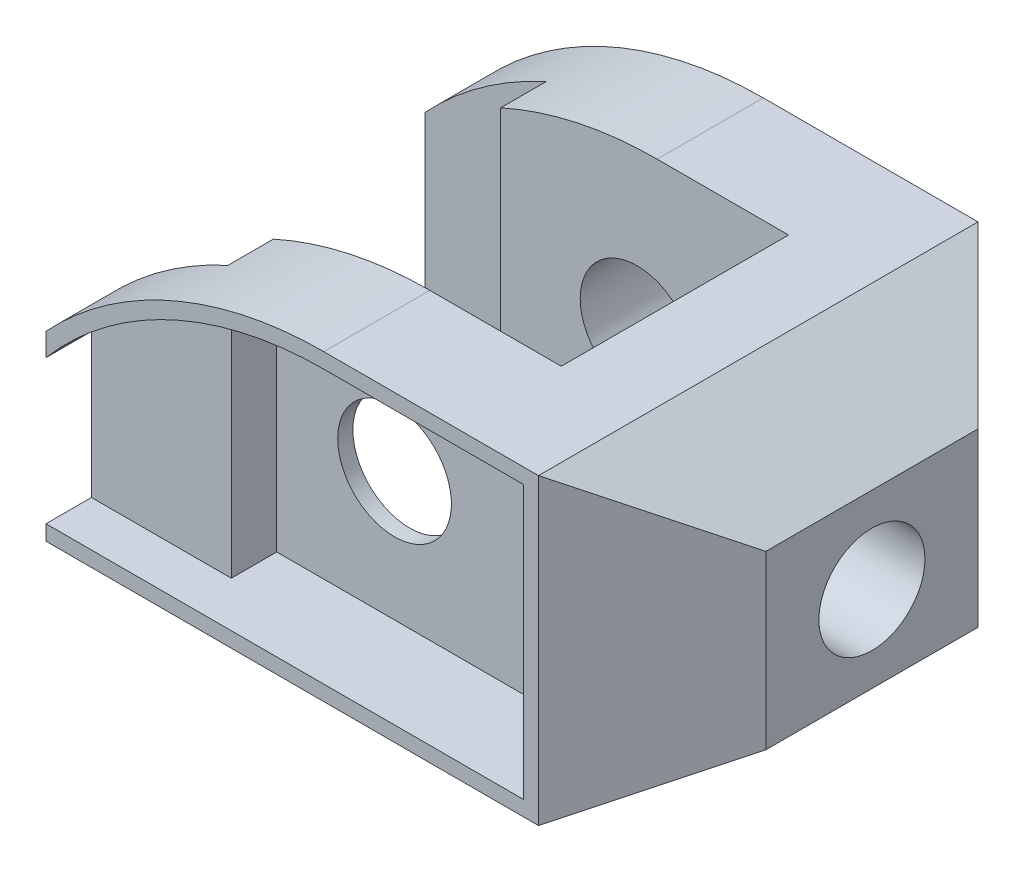
SolidWorks part; units mm, degrees
material "1060 Alloy"
ref_plane "Front Plane" through (0, 0, 0) normal (0, 0, 1) x (1, 0, 0)
ref_plane "Top Plane" through (0, 0, 0) normal (0, 1, 0) x (1, 0, 0)
ref_plane "Right Plane" through (0, 0, 0) normal (1, 0, 0) x (0, 0, -1)
sketch "Sketch2" plane through (0, 0, 0) normal (0, 0, 1) x (1, 0, 0)
  line L0 (0, 0) -> (0, 24)
  line L1 (0, 0) -> (65, 0)
  line L2 (65, 0) -> (80, 8.6603)
  line L3 (80, 8.6603) -> (80, 31.3397)
  line L4 (80, 31.3397) -> (65, 40)
  line L5 (65, 40) -> (36.6606, 40)
  arc A0 (0, 24) -> (36.6606, 40) centre (36.6606, -10) cw
  circle A1 centre (34, 19) radius 7.5
  dimension "D7" = 50
  dimension "D11" = 15
  dimension "D1" = 65
  dimension "D2" = 40
  dimension "D3" = 15
  dimension "D4" = 15
  dimension "D5" = 30
  dimension "D6" = 30
  dimension "D8" = 24
  dimension "D9" = 19
  dimension "D10" = 31
extrude "Boss-Extrude1" add sketch "Sketch2" along normal mid plane 58
sketch "Sketch3" plane through (0, 40, 0) normal (0, 1, 0) x (1, 0, 0)
  line L1 (80, -29) -> (80, 29) construction
  line L5 (0, 0) -> (80, 0) construction
  line L6 (65, 29) -> (80, 29)
  line L7 (80, 29) -> (80, 14)
  line L8 (80, 14) -> (65, 29)
  line L9 (0, 21) -> (16, 21)
  line L10 (0, -29) -> (0, 29) construction
  line L11 (16, 21) -> (16, 15)
  line L12 (16, 15) -> (54, 15)
  line L13 (54, 15) -> (54, -15)
  line L14 (65, -29) -> (65, 29) construction
  line L15 (36.6606, 29) -> (0, 29) construction
  line L16 (80, -29) -> (80, -14)
  line L17 (65, -29) -> (80, -29)
  line L18 (80, -14) -> (65, -29)
  line L19 (16, -15) -> (54, -15)
  line L20 (16, -21) -> (16, -15)
  line L21 (0, -21) -> (16, -21)
  line L22 (0, 21) -> (0, -21)
  point P26 (54, 0)
  dimension "D1" = 45
  dimension "D2" = 11
  dimension "D3" = 8
  dimension "D4" = 6
  dimension "D5" = 16
extrude "Cut-Extrude1" cut sketch "Sketch3" against normal through all
sketch "Sketch4" plane through (80, 0, 0) normal (1, 0, 0) x (0, 0, -1)
  line L0 (-14, 20) -> (14, 20) construction
  line L1 (-14, 8.6603) -> (-14, 31.3397) construction
  line L2 (14, 8.6603) -> (14, 31.3397) construction
  line L3 (0, 31.3397) -> (0, 8.6603) construction
  line L4 (-14, 31.3397) -> (14, 31.3397) construction
  line L5 (-14, 8.6603) -> (14, 8.6603) construction
  circle A0 centre (0, 20) radius 7
  dimension "D1" = 14
extrude "Cut-Extrude2" cut sketch "Sketch4" against normal through all
sketch "Sketch5" plane through (0, 0, 29) normal (0, 0, 1) x (1, 0, 0)
  line L4 (0, 24) -> (0, 0) construction
  line L5 (0, 20.9839) -> (0, 2)
  line L8 (2, 2) -> (63, 2)
  line L9 (63, 2) -> (63, 38)
  line L10 (63, 38) -> (36.6606, 38)
  line L11 (2, 23.2061) -> (2, 2)
  line L12 (0, 2) -> (63, 2)
  line L13 (63, 2) -> (63, 38)
  line L14 (63, 38) -> (36.6606, 38)
  arc A2 (36.6606, 38) -> (2, 23.2061) centre (36.6606, -10) ccw
  arc A3 (36.6606, 38) -> (0, 20.9839) centre (36.6606, -10) ccw
  point P6 (0, 0)
  dimension "D1" = 2
extrude "Cut-Extrude5" cut sketch "Sketch5" against normal blind 6
sketch "Sketch9" plane through (0, 0, 23) normal (0, 0, 1) x (1, 0, 0)
  line L3 (63, 2) -> (63, 38)
  line L4 (63, 38) -> (36.6606, 38)
  line L5 (18.452, 34.4122) -> (18.452, 2)
  line L6 (0, 2) -> (63, 2) construction
  line L7 (63, 2) -> (18.452, 2)
  arc A2 (36.6606, 38) -> (0, 20.9839) centre (36.6606, -10) ccw construction
  arc A3 (36.6606, 38) -> (18.452, 34.4122) centre (36.6606, -10) ccw
  point P9 (16.452, 33.5386)
  dimension "D1" = 2
extrude "Cut-Extrude7" cut sketch "Sketch9" against normal blind 6
equation "\"A\"= 58"
equation "\"B\"= 40"
equation "\"C\"= 65"
